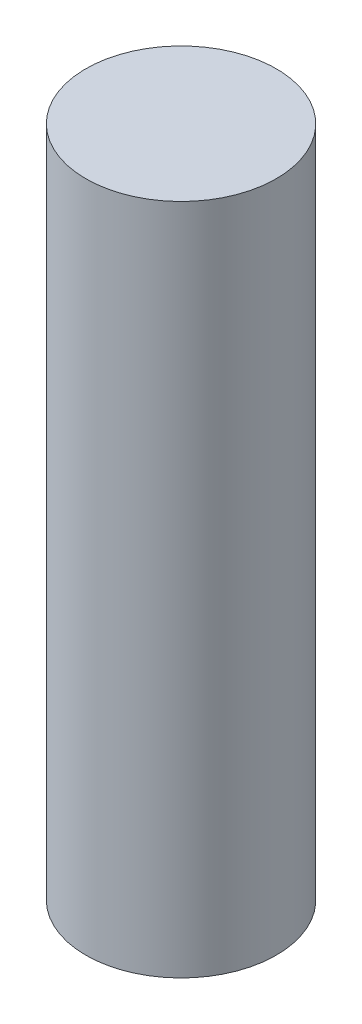
SolidWorks part; units mm, degrees
ref_plane "Front Plane" through (0, 0, 0) normal (0, 0, 1) x (1, 0, 0)
ref_plane "Top Plane" through (0, 0, 0) normal (0, 1, 0) x (1, 0, 0)
ref_plane "Right Plane" through (0, 0, 0) normal (1, 0, 0) x (0, 0, -1)
sketch "Sketch1" plane through (0, 0, 0) normal (0, 1, 0) x (1, 0, 0)
  circle A0 centre (0, 0) radius 8.5
  dimension "D1" = 17
extrude "Boss-Extrude1" add sketch "Sketch1" along normal blind 60
